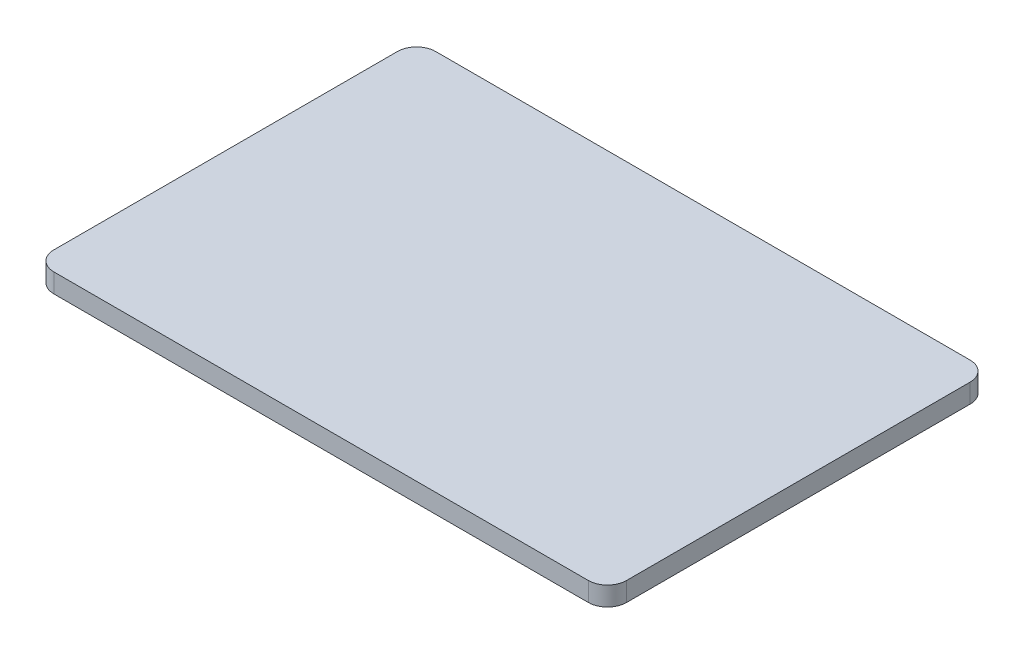
SolidWorks part; units mm, degrees
ref_plane "Front Plane" through (0, 0, 0) normal (0, 0, 1) x (1, 0, 0)
ref_plane "Top Plane" through (0, 0, 0) normal (0, 1, 0) x (1, 0, 0)
ref_plane "Right Plane" through (0, 0, 0) normal (1, 0, 0) x (0, 0, -1)
sketch "Sketch1" plane through (0, 0, 0) normal (0, 1, 0) x (1, 0, 0)
  line L1 (-75, -50) -> (75, -50)
  line L2 (-75, -50) -> (-75, 50)
  line L3 (-75, 50) -> (75, 50)
  line L4 (75, -50) -> (75, 50)
  line L5 (-75, -50) -> (75, 50) construction
  line L6 (-75, 50) -> (75, -50) construction
  point P0 (0, 0)
  dimension "D1" = 150
  dimension "D2" = 100
extrude "Boss-Extrude1" add sketch "Sketch1" along normal blind 5
fillet "Fillet1" radius 5 4 edges at (75, 2.5, -50) (75, 2.5, 50) (-75, 2.5, 50) (-75, 2.5, -50)
